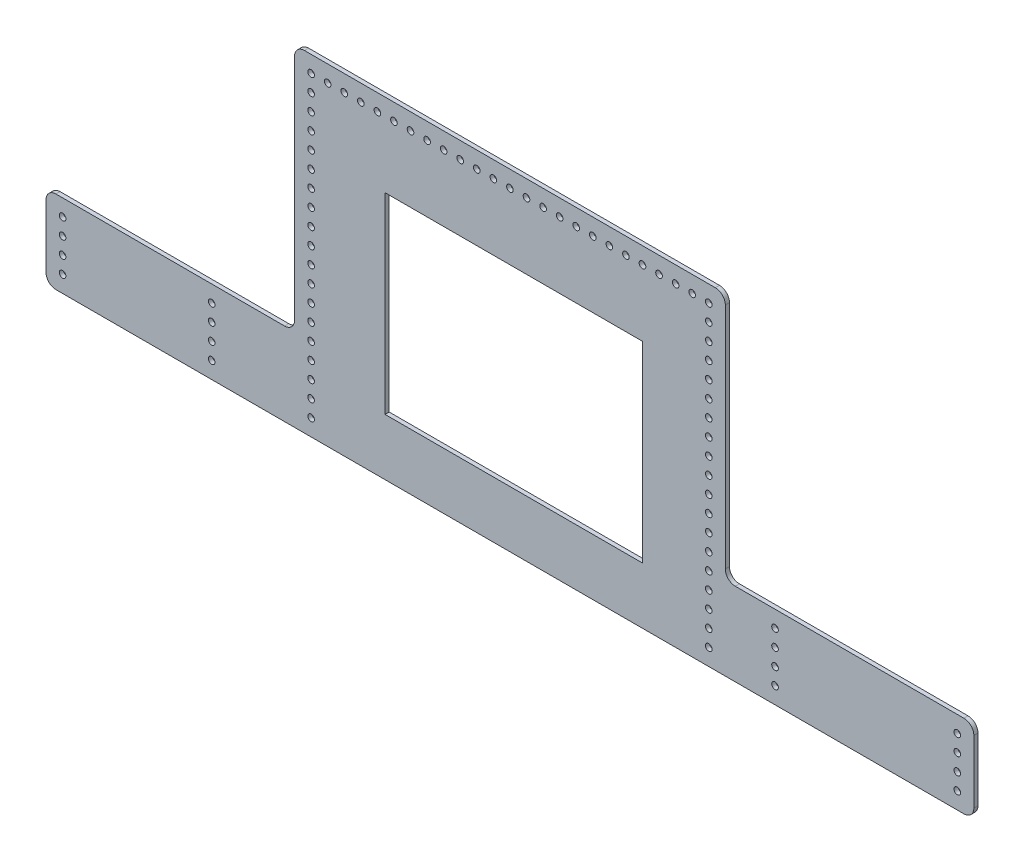
SolidWorks part; units mm, degrees
ref_plane "Front Plane" through (0, 0, 0) normal (0, 0, 1) x (1, 0, 0)
ref_plane "Top Plane" through (0, 0, 0) normal (0, 1, 0) x (1, 0, 0)
ref_plane "Right Plane" through (0, 0, 0) normal (1, 0, 0) x (0, 0, -1)
sketch "Sketch1" plane through (0, 0, 0) normal (0, 0, 1) x (1, 0, 0)
  line L1 (-309.8201, -121.697) -> (401.3799, -121.697)
  line L2 (-309.8201, -121.697) -> (-309.8201, -58.197)
  line L3 (-119.3201, 132.303) -> (210.8799, 132.303)
  line L4 (401.3799, -121.697) -> (401.3799, -58.197)
  line L11 (-309.8201, -58.197) -> (-119.3201, -58.197)
  line L12 (-119.3201, 132.303) -> (-119.3201, -58.197)
  line L15 (401.3799, -58.197) -> (210.8799, -58.197)
  line L16 (210.8799, 132.303) -> (210.8799, -58.197)
  line L17 (-49.9208, 68.803) -> (147.3799, 68.803)
  line L18 (-49.9208, 68.803) -> (-49.9208, -78.3706)
  line L19 (-49.9208, -78.3706) -> (147.3799, -78.3706)
  line L20 (147.3799, 68.803) -> (147.3799, -78.3706)
  circle A0 centre (-297.1201, -70.897) radius 2.54
  circle A1 centre (388.6799, -70.897) radius 2.54
  circle A2 centre (388.6799, -83.597) radius 2.54
  circle A3 centre (388.6799, -96.297) radius 2.54
  circle A4 centre (388.6799, -108.997) radius 2.54
  circle A6 centre (-297.1201, -83.597) radius 2.54
  circle A7 centre (-297.1201, -96.297) radius 2.54
  circle A8 centre (-297.1201, -108.997) radius 2.54
  circle A73 centre (-182.8201, -70.897) radius 2.54
  circle A74 centre (248.9799, -70.897) radius 2.54
  circle A75 centre (-297.1201, -121.697) radius 2.54 [skipped]
  circle A76 centre (388.6799, -121.697) radius 2.54 [skipped]
  circle A77 centre (248.9799, -83.597) radius 2.54
  circle A78 centre (248.9799, -96.297) radius 2.54
  circle A79 centre (248.9799, -108.997) radius 2.54
  circle A80 centre (-182.8201, -83.597) radius 2.54
  circle A86 centre (-182.8201, -96.297) radius 2.54
  circle A87 centre (-182.8201, -108.997) radius 2.54
  circle A104 centre (-106.6201, 119.603) radius 2.54
  circle A105 centre (-93.9201, 119.603) radius 2.54
  circle A106 centre (-81.2201, 119.603) radius 2.54
  circle A107 centre (-68.5201, 119.603) radius 2.54
  circle A108 centre (-55.8201, 119.603) radius 2.54
  circle A109 centre (-43.1201, 119.603) radius 2.54
  circle A110 centre (-30.4201, 119.603) radius 2.54
  circle A111 centre (-17.7201, 119.603) radius 2.54
  circle A112 centre (-5.0201, 119.603) radius 2.54
  circle A113 centre (7.6799, 119.603) radius 2.54
  circle A114 centre (20.3799, 119.603) radius 2.54
  circle A115 centre (33.0799, 119.603) radius 2.54
  circle A116 centre (45.7799, 119.603) radius 2.54
  circle A117 centre (58.4799, 119.603) radius 2.54
  circle A118 centre (71.1799, 119.603) radius 2.54
  circle A119 centre (83.8799, 119.603) radius 2.54
  circle A120 centre (96.5799, 119.603) radius 2.54
  circle A121 centre (109.2799, 119.603) radius 2.54
  circle A122 centre (121.9799, 119.603) radius 2.54
  circle A123 centre (134.6799, 119.603) radius 2.54
  circle A124 centre (147.3799, 119.603) radius 2.54
  circle A125 centre (160.0799, 119.603) radius 2.54
  circle A126 centre (172.7799, 119.603) radius 2.54
  circle A127 centre (185.4799, 119.603) radius 2.54
  circle A128 centre (198.1799, 119.603) radius 2.54
  circle A152 centre (198.1799, 106.903) radius 2.54
  circle A176 centre (198.1799, 94.203) radius 2.54
  circle A200 centre (198.1799, 81.503) radius 2.54
  circle A224 centre (198.1799, 68.803) radius 2.54
  circle A248 centre (198.1799, 56.103) radius 2.54
  circle A272 centre (198.1799, 43.403) radius 2.54
  circle A296 centre (198.1799, 30.703) radius 2.54
  circle A320 centre (198.1799, 18.003) radius 2.54
  circle A344 centre (198.1799, 5.303) radius 2.54
  circle A368 centre (198.1799, -7.397) radius 2.54
  circle A392 centre (198.1799, -20.097) radius 2.54
  circle A416 centre (198.1799, -32.797) radius 2.54
  circle A440 centre (198.1799, -45.497) radius 2.54
  circle A464 centre (198.1799, -58.197) radius 2.54
  circle A488 centre (198.1799, -70.897) radius 2.54
  circle A512 centre (198.1799, -83.597) radius 2.54
  circle A536 centre (198.1799, -96.297) radius 2.54
  circle A560 centre (198.1799, -108.997) radius 2.54
  circle A561 centre (-106.6201, 106.903) radius 2.54
  circle A562 centre (-106.6201, 94.203) radius 2.54
  circle A563 centre (-106.6201, 81.503) radius 2.54
  circle A564 centre (-106.6201, 68.803) radius 2.54
  circle A565 centre (-106.6201, 56.103) radius 2.54
  circle A566 centre (-106.6201, 43.403) radius 2.54
  circle A567 centre (-106.6201, 30.703) radius 2.54
  circle A568 centre (-106.6201, 18.003) radius 2.54
  circle A569 centre (-106.6201, 5.303) radius 2.54
  circle A570 centre (-106.6201, -7.397) radius 2.54
  circle A571 centre (-106.6201, -20.097) radius 2.54
  circle A572 centre (-106.6201, -32.797) radius 2.54
  circle A573 centre (-106.6201, -45.497) radius 2.54
  circle A574 centre (-106.6201, -58.197) radius 2.54
  circle A575 centre (-106.6201, -70.897) radius 2.54
  circle A576 centre (-106.6201, -83.597) radius 2.54
  circle A577 centre (-106.6201, -96.297) radius 2.54
  circle A578 centre (-106.6201, -108.997) radius 2.54
  circle A579 centre (-93.9201, 106.903) radius 2.54 [skipped]
  circle A580 centre (-81.2201, 106.903) radius 2.54 [skipped]
  circle A581 centre (-68.5201, 106.903) radius 2.54 [skipped]
  circle A582 centre (-55.8201, 106.903) radius 2.54 [skipped]
  circle A583 centre (-43.1201, 106.903) radius 2.54 [skipped]
  circle A584 centre (-30.4201, 106.903) radius 2.54 [skipped]
  circle A585 centre (-17.7201, 106.903) radius 2.54 [skipped]
  circle A586 centre (-5.0201, 106.903) radius 2.54 [skipped]
  circle A587 centre (7.6799, 106.903) radius 2.54 [skipped]
  circle A588 centre (20.3799, 106.903) radius 2.54 [skipped]
  circle A589 centre (33.0799, 106.903) radius 2.54 [skipped]
  circle A590 centre (45.7799, 106.903) radius 2.54 [skipped]
  circle A591 centre (58.4799, 106.903) radius 2.54 [skipped]
  circle A592 centre (71.1799, 106.903) radius 2.54 [skipped]
  circle A593 centre (83.8799, 106.903) radius 2.54 [skipped]
  circle A594 centre (96.5799, 106.903) radius 2.54 [skipped]
  circle A595 centre (109.2799, 106.903) radius 2.54 [skipped]
  circle A596 centre (121.9799, 106.903) radius 2.54 [skipped]
  circle A597 centre (134.6799, 106.903) radius 2.54 [skipped]
  circle A598 centre (147.3799, 106.903) radius 2.54 [skipped]
  circle A599 centre (160.0799, 106.903) radius 2.54 [skipped]
  circle A600 centre (172.7799, 106.903) radius 2.54 [skipped]
  circle A601 centre (185.4799, 106.903) radius 2.54 [skipped]
  circle A602 centre (-93.9201, 94.203) radius 2.54 [skipped]
  circle A603 centre (-81.2201, 94.203) radius 2.54 [skipped]
  circle A604 centre (-68.5201, 94.203) radius 2.54 [skipped]
  circle A605 centre (-55.8201, 94.203) radius 2.54 [skipped]
  circle A606 centre (-43.1201, 94.203) radius 2.54 [skipped]
  circle A607 centre (-30.4201, 94.203) radius 2.54 [skipped]
  circle A608 centre (-17.7201, 94.203) radius 2.54 [skipped]
  circle A609 centre (-5.0201, 94.203) radius 2.54 [skipped]
  circle A610 centre (7.6799, 94.203) radius 2.54 [skipped]
  circle A611 centre (20.3799, 94.203) radius 2.54 [skipped]
  circle A612 centre (33.0799, 94.203) radius 2.54 [skipped]
  circle A613 centre (45.7799, 94.203) radius 2.54 [skipped]
  circle A614 centre (58.4799, 94.203) radius 2.54 [skipped]
  circle A615 centre (71.1799, 94.203) radius 2.54 [skipped]
  circle A616 centre (83.8799, 94.203) radius 2.54 [skipped]
  circle A617 centre (96.5799, 94.203) radius 2.54 [skipped]
  circle A618 centre (109.2799, 94.203) radius 2.54 [skipped]
  circle A619 centre (121.9799, 94.203) radius 2.54 [skipped]
  circle A620 centre (134.6799, 94.203) radius 2.54 [skipped]
  circle A621 centre (147.3799, 94.203) radius 2.54 [skipped]
  circle A622 centre (160.0799, 94.203) radius 2.54 [skipped]
  circle A623 centre (172.7799, 94.203) radius 2.54 [skipped]
  circle A624 centre (185.4799, 94.203) radius 2.54 [skipped]
  circle A625 centre (-93.9201, 81.503) radius 2.54 [skipped]
  circle A626 centre (-81.2201, 81.503) radius 2.54 [skipped]
  circle A627 centre (-68.5201, 81.503) radius 2.54 [skipped]
  circle A628 centre (-55.8201, 81.503) radius 2.54 [skipped]
  circle A629 centre (-43.1201, 81.503) radius 2.54 [skipped]
  circle A630 centre (-30.4201, 81.503) radius 2.54 [skipped]
  circle A631 centre (-17.7201, 81.503) radius 2.54 [skipped]
  circle A632 centre (-5.0201, 81.503) radius 2.54 [skipped]
  circle A633 centre (7.6799, 81.503) radius 2.54 [skipped]
  circle A634 centre (20.3799, 81.503) radius 2.54 [skipped]
  circle A635 centre (33.0799, 81.503) radius 2.54 [skipped]
  circle A636 centre (45.7799, 81.503) radius 2.54 [skipped]
  circle A637 centre (58.4799, 81.503) radius 2.54 [skipped]
  circle A638 centre (71.1799, 81.503) radius 2.54 [skipped]
  circle A639 centre (83.8799, 81.503) radius 2.54 [skipped]
  circle A640 centre (96.5799, 81.503) radius 2.54 [skipped]
  circle A641 centre (109.2799, 81.503) radius 2.54 [skipped]
  circle A642 centre (121.9799, 81.503) radius 2.54 [skipped]
  circle A643 centre (134.6799, 81.503) radius 2.54 [skipped]
  circle A644 centre (147.3799, 81.503) radius 2.54 [skipped]
  circle A645 centre (160.0799, 81.503) radius 2.54 [skipped]
  circle A646 centre (172.7799, 81.503) radius 2.54 [skipped]
  circle A647 centre (185.4799, 81.503) radius 2.54 [skipped]
  circle A648 centre (-93.9201, 68.803) radius 2.54 [skipped]
  circle A649 centre (-81.2201, 68.803) radius 2.54 [skipped]
  circle A650 centre (-68.5201, 68.803) radius 2.54 [skipped]
  circle A651 centre (-55.8201, 68.803) radius 2.54 [skipped]
  circle A652 centre (-43.1201, 68.803) radius 2.54 [skipped]
  circle A653 centre (-30.4201, 68.803) radius 2.54 [skipped]
  circle A654 centre (-17.7201, 68.803) radius 2.54 [skipped]
  circle A655 centre (-5.0201, 68.803) radius 2.54 [skipped]
  circle A656 centre (7.6799, 68.803) radius 2.54 [skipped]
  circle A657 centre (20.3799, 68.803) radius 2.54 [skipped]
  circle A658 centre (33.0799, 68.803) radius 2.54 [skipped]
  circle A659 centre (45.7799, 68.803) radius 2.54 [skipped]
  circle A660 centre (58.4799, 68.803) radius 2.54 [skipped]
  circle A661 centre (71.1799, 68.803) radius 2.54 [skipped]
  circle A662 centre (83.8799, 68.803) radius 2.54 [skipped]
  circle A663 centre (96.5799, 68.803) radius 2.54 [skipped]
  circle A664 centre (109.2799, 68.803) radius 2.54 [skipped]
  circle A665 centre (121.9799, 68.803) radius 2.54 [skipped]
  circle A666 centre (134.6799, 68.803) radius 2.54 [skipped]
  circle A667 centre (147.3799, 68.803) radius 2.54 [skipped]
  circle A668 centre (160.0799, 68.803) radius 2.54 [skipped]
  circle A669 centre (172.7799, 68.803) radius 2.54 [skipped]
  circle A670 centre (185.4799, 68.803) radius 2.54 [skipped]
  circle A671 centre (-93.9201, 56.103) radius 2.54 [skipped]
  circle A672 centre (-81.2201, 56.103) radius 2.54 [skipped]
  circle A673 centre (-68.5201, 56.103) radius 2.54 [skipped]
  circle A674 centre (-55.8201, 56.103) radius 2.54 [skipped]
  circle A675 centre (-43.1201, 56.103) radius 2.54 [skipped]
  circle A676 centre (-30.4201, 56.103) radius 2.54 [skipped]
  circle A677 centre (-17.7201, 56.103) radius 2.54 [skipped]
  circle A678 centre (-5.0201, 56.103) radius 2.54 [skipped]
  circle A679 centre (7.6799, 56.103) radius 2.54 [skipped]
  circle A680 centre (20.3799, 56.103) radius 2.54 [skipped]
  circle A681 centre (33.0799, 56.103) radius 2.54 [skipped]
  circle A682 centre (45.7799, 56.103) radius 2.54 [skipped]
  circle A683 centre (58.4799, 56.103) radius 2.54 [skipped]
  circle A684 centre (71.1799, 56.103) radius 2.54 [skipped]
  circle A685 centre (83.8799, 56.103) radius 2.54 [skipped]
  circle A686 centre (96.5799, 56.103) radius 2.54 [skipped]
  circle A687 centre (109.2799, 56.103) radius 2.54 [skipped]
  circle A688 centre (121.9799, 56.103) radius 2.54 [skipped]
  circle A689 centre (134.6799, 56.103) radius 2.54 [skipped]
  circle A690 centre (147.3799, 56.103) radius 2.54 [skipped]
  circle A691 centre (160.0799, 56.103) radius 2.54 [skipped]
  circle A692 centre (172.7799, 56.103) radius 2.54 [skipped]
  circle A693 centre (185.4799, 56.103) radius 2.54 [skipped]
  circle A694 centre (-93.9201, 43.403) radius 2.54 [skipped]
  circle A695 centre (-81.2201, 43.403) radius 2.54 [skipped]
  circle A696 centre (-68.5201, 43.403) radius 2.54 [skipped]
  circle A697 centre (-55.8201, 43.403) radius 2.54 [skipped]
  circle A698 centre (-43.1201, 43.403) radius 2.54 [skipped]
  circle A699 centre (-30.4201, 43.403) radius 2.54 [skipped]
  circle A700 centre (-17.7201, 43.403) radius 2.54 [skipped]
  circle A701 centre (-5.0201, 43.403) radius 2.54 [skipped]
  circle A702 centre (7.6799, 43.403) radius 2.54 [skipped]
  circle A703 centre (20.3799, 43.403) radius 2.54 [skipped]
  circle A704 centre (33.0799, 43.403) radius 2.54 [skipped]
  circle A705 centre (45.7799, 43.403) radius 2.54 [skipped]
  circle A706 centre (58.4799, 43.403) radius 2.54 [skipped]
  circle A707 centre (71.1799, 43.403) radius 2.54 [skipped]
  circle A708 centre (83.8799, 43.403) radius 2.54 [skipped]
  circle A709 centre (96.5799, 43.403) radius 2.54 [skipped]
  circle A710 centre (109.2799, 43.403) radius 2.54 [skipped]
  circle A711 centre (121.9799, 43.403) radius 2.54 [skipped]
  circle A712 centre (134.6799, 43.403) radius 2.54 [skipped]
  circle A713 centre (147.3799, 43.403) radius 2.54 [skipped]
  circle A714 centre (160.0799, 43.403) radius 2.54 [skipped]
  circle A715 centre (172.7799, 43.403) radius 2.54 [skipped]
  circle A716 centre (185.4799, 43.403) radius 2.54 [skipped]
  circle A717 centre (-93.9201, 30.703) radius 2.54 [skipped]
  circle A718 centre (-81.2201, 30.703) radius 2.54 [skipped]
  circle A719 centre (-68.5201, 30.703) radius 2.54 [skipped]
  circle A720 centre (-55.8201, 30.703) radius 2.54 [skipped]
  circle A721 centre (-43.1201, 30.703) radius 2.54 [skipped]
  circle A722 centre (-30.4201, 30.703) radius 2.54 [skipped]
  circle A723 centre (-17.7201, 30.703) radius 2.54 [skipped]
  circle A724 centre (-5.0201, 30.703) radius 2.54 [skipped]
  circle A725 centre (7.6799, 30.703) radius 2.54 [skipped]
  circle A726 centre (20.3799, 30.703) radius 2.54 [skipped]
  circle A727 centre (33.0799, 30.703) radius 2.54 [skipped]
  circle A728 centre (45.7799, 30.703) radius 2.54 [skipped]
  circle A729 centre (58.4799, 30.703) radius 2.54 [skipped]
  circle A730 centre (71.1799, 30.703) radius 2.54 [skipped]
  circle A731 centre (83.8799, 30.703) radius 2.54 [skipped]
  circle A732 centre (96.5799, 30.703) radius 2.54 [skipped]
  circle A733 centre (109.2799, 30.703) radius 2.54 [skipped]
  circle A734 centre (121.9799, 30.703) radius 2.54 [skipped]
  circle A735 centre (134.6799, 30.703) radius 2.54 [skipped]
  circle A736 centre (147.3799, 30.703) radius 2.54 [skipped]
  circle A737 centre (160.0799, 30.703) radius 2.54 [skipped]
  circle A738 centre (172.7799, 30.703) radius 2.54 [skipped]
  circle A739 centre (-93.9201, 18.003) radius 2.54 [skipped]
  circle A740 centre (-81.2201, 18.003) radius 2.54 [skipped]
  circle A741 centre (-68.5201, 18.003) radius 2.54 [skipped]
  circle A742 centre (-55.8201, 18.003) radius 2.54 [skipped]
  circle A743 centre (-43.1201, 18.003) radius 2.54 [skipped]
  circle A744 centre (-30.4201, 18.003) radius 2.54 [skipped]
  circle A745 centre (-17.7201, 18.003) radius 2.54 [skipped]
  circle A746 centre (-5.0201, 18.003) radius 2.54 [skipped]
  circle A747 centre (7.6799, 18.003) radius 2.54 [skipped]
  circle A748 centre (20.3799, 18.003) radius 2.54 [skipped]
  circle A749 centre (33.0799, 18.003) radius 2.54 [skipped]
  circle A750 centre (45.7799, 18.003) radius 2.54 [skipped]
  circle A751 centre (58.4799, 18.003) radius 2.54 [skipped]
  circle A752 centre (71.1799, 18.003) radius 2.54 [skipped]
  circle A753 centre (83.8799, 18.003) radius 2.54 [skipped]
  circle A754 centre (96.5799, 18.003) radius 2.54 [skipped]
  circle A755 centre (109.2799, 18.003) radius 2.54 [skipped]
  circle A756 centre (121.9799, 18.003) radius 2.54 [skipped]
  circle A757 centre (134.6799, 18.003) radius 2.54 [skipped]
  circle A758 centre (147.3799, 18.003) radius 2.54 [skipped]
  circle A759 centre (160.0799, 18.003) radius 2.54 [skipped]
  circle A760 centre (172.7799, 18.003) radius 2.54 [skipped]
  circle A761 centre (185.4799, 18.003) radius 2.54 [skipped]
  circle A762 centre (-93.9201, 5.303) radius 2.54 [skipped]
  circle A763 centre (-81.2201, 5.303) radius 2.54 [skipped]
  circle A764 centre (-68.5201, 5.303) radius 2.54 [skipped]
  circle A765 centre (-55.8201, 5.303) radius 2.54 [skipped]
  circle A766 centre (-43.1201, 5.303) radius 2.54 [skipped]
  circle A767 centre (-30.4201, 5.303) radius 2.54 [skipped]
  circle A768 centre (-17.7201, 5.303) radius 2.54 [skipped]
  circle A769 centre (-5.0201, 5.303) radius 2.54 [skipped]
  circle A770 centre (7.6799, 5.303) radius 2.54 [skipped]
  circle A771 centre (20.3799, 5.303) radius 2.54 [skipped]
  circle A772 centre (33.0799, 5.303) radius 2.54 [skipped]
  circle A773 centre (45.7799, 5.303) radius 2.54 [skipped]
  circle A774 centre (58.4799, 5.303) radius 2.54 [skipped]
  circle A775 centre (71.1799, 5.303) radius 2.54 [skipped]
  circle A776 centre (83.8799, 5.303) radius 2.54 [skipped]
  circle A777 centre (96.5799, 5.303) radius 2.54 [skipped]
  circle A778 centre (109.2799, 5.303) radius 2.54 [skipped]
  circle A779 centre (121.9799, 5.303) radius 2.54 [skipped]
  circle A780 centre (134.6799, 5.303) radius 2.54 [skipped]
  circle A781 centre (147.3799, 5.303) radius 2.54 [skipped]
  circle A782 centre (160.0799, 5.303) radius 2.54 [skipped]
  circle A783 centre (172.7799, 5.303) radius 2.54 [skipped]
  circle A784 centre (185.4799, 5.303) radius 2.54 [skipped]
  circle A785 centre (-93.9201, -7.397) radius 2.54 [skipped]
  circle A786 centre (-81.2201, -7.397) radius 2.54 [skipped]
  circle A787 centre (-68.5201, -7.397) radius 2.54 [skipped]
  circle A788 centre (-55.8201, -7.397) radius 2.54 [skipped]
  circle A789 centre (-43.1201, -7.397) radius 2.54 [skipped]
  circle A790 centre (-30.4201, -7.397) radius 2.54 [skipped]
  circle A791 centre (-17.7201, -7.397) radius 2.54 [skipped]
  circle A792 centre (-5.0201, -7.397) radius 2.54 [skipped]
  circle A793 centre (7.6799, -7.397) radius 2.54 [skipped]
  circle A794 centre (20.3799, -7.397) radius 2.54 [skipped]
  circle A795 centre (33.0799, -7.397) radius 2.54 [skipped]
  circle A796 centre (45.7799, -7.397) radius 2.54 [skipped]
  circle A797 centre (58.4799, -7.397) radius 2.54 [skipped]
  circle A798 centre (71.1799, -7.397) radius 2.54 [skipped]
  circle A799 centre (83.8799, -7.397) radius 2.54 [skipped]
  circle A800 centre (96.5799, -7.397) radius 2.54 [skipped]
  circle A801 centre (109.2799, -7.397) radius 2.54 [skipped]
  circle A802 centre (121.9799, -7.397) radius 2.54 [skipped]
  circle A803 centre (134.6799, -7.397) radius 2.54 [skipped]
  circle A804 centre (147.3799, -7.397) radius 2.54 [skipped]
  circle A805 centre (160.0799, -7.397) radius 2.54 [skipped]
  circle A806 centre (172.7799, -7.397) radius 2.54 [skipped]
  circle A807 centre (185.4799, -7.397) radius 2.54 [skipped]
  circle A808 centre (-93.9201, -20.097) radius 2.54 [skipped]
  circle A809 centre (-81.2201, -20.097) radius 2.54 [skipped]
  circle A810 centre (-68.5201, -20.097) radius 2.54 [skipped]
  circle A811 centre (-55.8201, -20.097) radius 2.54 [skipped]
  circle A812 centre (-43.1201, -20.097) radius 2.54 [skipped]
  circle A813 centre (-30.4201, -20.097) radius 2.54 [skipped]
  circle A814 centre (-17.7201, -20.097) radius 2.54 [skipped]
  circle A815 centre (-5.0201, -20.097) radius 2.54 [skipped]
  circle A816 centre (7.6799, -20.097) radius 2.54 [skipped]
  circle A817 centre (20.3799, -20.097) radius 2.54 [skipped]
  circle A818 centre (33.0799, -20.097) radius 2.54 [skipped]
  circle A819 centre (45.7799, -20.097) radius 2.54 [skipped]
  circle A820 centre (58.4799, -20.097) radius 2.54 [skipped]
  circle A821 centre (71.1799, -20.097) radius 2.54 [skipped]
  circle A822 centre (83.8799, -20.097) radius 2.54 [skipped]
  circle A823 centre (96.5799, -20.097) radius 2.54 [skipped]
  circle A824 centre (109.2799, -20.097) radius 2.54 [skipped]
  circle A825 centre (121.9799, -20.097) radius 2.54 [skipped]
  circle A826 centre (134.6799, -20.097) radius 2.54 [skipped]
  circle A827 centre (147.3799, -20.097) radius 2.54 [skipped]
  circle A828 centre (160.0799, -20.097) radius 2.54 [skipped]
  circle A829 centre (172.7799, -20.097) radius 2.54 [skipped]
  circle A830 centre (185.4799, -20.097) radius 2.54 [skipped]
  circle A831 centre (-93.9201, -32.797) radius 2.54 [skipped]
  circle A832 centre (-81.2201, -32.797) radius 2.54 [skipped]
  circle A833 centre (-68.5201, -32.797) radius 2.54 [skipped]
  circle A834 centre (-55.8201, -32.797) radius 2.54 [skipped]
  circle A835 centre (-43.1201, -32.797) radius 2.54 [skipped]
  circle A836 centre (-30.4201, -32.797) radius 2.54 [skipped]
  circle A837 centre (-17.7201, -32.797) radius 2.54 [skipped]
  circle A838 centre (-5.0201, -32.797) radius 2.54 [skipped]
  circle A839 centre (7.6799, -32.797) radius 2.54 [skipped]
  circle A840 centre (20.3799, -32.797) radius 2.54 [skipped]
  circle A841 centre (33.0799, -32.797) radius 2.54 [skipped]
  circle A842 centre (45.7799, -32.797) radius 2.54 [skipped]
  circle A843 centre (58.4799, -32.797) radius 2.54 [skipped]
  circle A844 centre (71.1799, -32.797) radius 2.54 [skipped]
  circle A845 centre (83.8799, -32.797) radius 2.54 [skipped]
  circle A846 centre (96.5799, -32.797) radius 2.54 [skipped]
  circle A847 centre (109.2799, -32.797) radius 2.54 [skipped]
  circle A848 centre (121.9799, -32.797) radius 2.54 [skipped]
  circle A849 centre (134.6799, -32.797) radius 2.54 [skipped]
  circle A850 centre (147.3799, -32.797) radius 2.54 [skipped]
  circle A851 centre (160.0799, -32.797) radius 2.54 [skipped]
  circle A852 centre (172.7799, -32.797) radius 2.54 [skipped]
  circle A853 centre (185.4799, -32.797) radius 2.54 [skipped]
  circle A854 centre (-93.9201, -45.497) radius 2.54 [skipped]
  circle A855 centre (-81.2201, -45.497) radius 2.54 [skipped]
  circle A856 centre (-68.5201, -45.497) radius 2.54 [skipped]
  circle A857 centre (-55.8201, -45.497) radius 2.54 [skipped]
  circle A858 centre (-43.1201, -45.497) radius 2.54 [skipped]
  circle A859 centre (-30.4201, -45.497) radius 2.54 [skipped]
  circle A860 centre (-17.7201, -45.497) radius 2.54 [skipped]
  circle A861 centre (-5.0201, -45.497) radius 2.54 [skipped]
  circle A862 centre (7.6799, -45.497) radius 2.54 [skipped]
  circle A863 centre (20.3799, -45.497) radius 2.54 [skipped]
  circle A864 centre (33.0799, -45.497) radius 2.54 [skipped]
  circle A865 centre (45.7799, -45.497) radius 2.54 [skipped]
  circle A866 centre (58.4799, -45.497) radius 2.54 [skipped]
  circle A867 centre (71.1799, -45.497) radius 2.54 [skipped]
  circle A868 centre (83.8799, -45.497) radius 2.54 [skipped]
  circle A869 centre (96.5799, -45.497) radius 2.54 [skipped]
  circle A870 centre (109.2799, -45.497) radius 2.54 [skipped]
  circle A871 centre (121.9799, -45.497) radius 2.54 [skipped]
  circle A872 centre (134.6799, -45.497) radius 2.54 [skipped]
  circle A873 centre (147.3799, -45.497) radius 2.54 [skipped]
  circle A874 centre (160.0799, -45.497) radius 2.54 [skipped]
  circle A875 centre (172.7799, -45.497) radius 2.54 [skipped]
  circle A876 centre (185.4799, -45.497) radius 2.54 [skipped]
  circle A877 centre (-93.9201, -58.197) radius 2.54 [skipped]
  circle A878 centre (-81.2201, -58.197) radius 2.54 [skipped]
  circle A879 centre (-68.5201, -58.197) radius 2.54 [skipped]
  circle A880 centre (-55.8201, -58.197) radius 2.54 [skipped]
  circle A881 centre (-43.1201, -58.197) radius 2.54 [skipped]
  circle A882 centre (-30.4201, -58.197) radius 2.54 [skipped]
  circle A883 centre (-17.7201, -58.197) radius 2.54 [skipped]
  circle A884 centre (-5.0201, -58.197) radius 2.54 [skipped]
  circle A885 centre (7.6799, -58.197) radius 2.54 [skipped]
  circle A886 centre (20.3799, -58.197) radius 2.54 [skipped]
  circle A887 centre (33.0799, -58.197) radius 2.54 [skipped]
  circle A888 centre (45.7799, -58.197) radius 2.54 [skipped]
  circle A889 centre (58.4799, -58.197) radius 2.54 [skipped]
  circle A890 centre (71.1799, -58.197) radius 2.54 [skipped]
  circle A891 centre (83.8799, -58.197) radius 2.54 [skipped]
  circle A892 centre (96.5799, -58.197) radius 2.54 [skipped]
  circle A893 centre (109.2799, -58.197) radius 2.54 [skipped]
  circle A894 centre (121.9799, -58.197) radius 2.54 [skipped]
  circle A895 centre (134.6799, -58.197) radius 2.54 [skipped]
  circle A896 centre (147.3799, -58.197) radius 2.54 [skipped]
  circle A897 centre (160.0799, -58.197) radius 2.54 [skipped]
  circle A898 centre (172.7799, -58.197) radius 2.54 [skipped]
  circle A899 centre (185.4799, -58.197) radius 2.54 [skipped]
  circle A900 centre (-93.9201, -70.897) radius 2.54 [skipped]
  circle A901 centre (-81.2201, -70.897) radius 2.54 [skipped]
  circle A902 centre (-68.5201, -70.897) radius 2.54 [skipped]
  circle A903 centre (-55.8201, -70.897) radius 2.54 [skipped]
  circle A904 centre (-43.1201, -70.897) radius 2.54 [skipped]
  circle A905 centre (-30.4201, -70.897) radius 2.54 [skipped]
  circle A906 centre (-17.7201, -70.897) radius 2.54 [skipped]
  circle A907 centre (-5.0201, -70.897) radius 2.54 [skipped]
  circle A908 centre (7.6799, -70.897) radius 2.54 [skipped]
  circle A909 centre (20.3799, -70.897) radius 2.54 [skipped]
  circle A910 centre (33.0799, -70.897) radius 2.54 [skipped]
  circle A911 centre (45.7799, -70.897) radius 2.54 [skipped]
  circle A912 centre (58.4799, -70.897) radius 2.54 [skipped]
  circle A913 centre (71.1799, -70.897) radius 2.54 [skipped]
  circle A914 centre (83.8799, -70.897) radius 2.54 [skipped]
  circle A915 centre (96.5799, -70.897) radius 2.54 [skipped]
  circle A916 centre (109.2799, -70.897) radius 2.54 [skipped]
  circle A917 centre (121.9799, -70.897) radius 2.54 [skipped]
  circle A918 centre (134.6799, -70.897) radius 2.54 [skipped]
  circle A919 centre (147.3799, -70.897) radius 2.54 [skipped]
  circle A920 centre (160.0799, -70.897) radius 2.54 [skipped]
  circle A921 centre (172.7799, -70.897) radius 2.54 [skipped]
  circle A922 centre (185.4799, -70.897) radius 2.54 [skipped]
  circle A923 centre (-93.9201, -83.597) radius 2.54 [skipped]
  circle A924 centre (-81.2201, -83.597) radius 2.54 [skipped]
  circle A925 centre (-68.5201, -83.597) radius 2.54 [skipped]
  circle A926 centre (-55.8201, -83.597) radius 2.54 [skipped]
  circle A927 centre (-43.1201, -83.597) radius 2.54 [skipped]
  circle A928 centre (-30.4201, -83.597) radius 2.54 [skipped]
  circle A929 centre (-17.7201, -83.597) radius 2.54 [skipped]
  circle A930 centre (-5.0201, -83.597) radius 2.54 [skipped]
  circle A931 centre (7.6799, -83.597) radius 2.54 [skipped]
  circle A932 centre (20.3799, -83.597) radius 2.54 [skipped]
  circle A933 centre (33.0799, -83.597) radius 2.54 [skipped]
  circle A934 centre (45.7799, -83.597) radius 2.54 [skipped]
  circle A935 centre (58.4799, -83.597) radius 2.54 [skipped]
  circle A936 centre (71.1799, -83.597) radius 2.54 [skipped]
  circle A937 centre (83.8799, -83.597) radius 2.54 [skipped]
  circle A938 centre (96.5799, -83.597) radius 2.54 [skipped]
  circle A939 centre (109.2799, -83.597) radius 2.54 [skipped]
  circle A940 centre (121.9799, -83.597) radius 2.54 [skipped]
  circle A941 centre (134.6799, -83.597) radius 2.54 [skipped]
  circle A942 centre (147.3799, -83.597) radius 2.54 [skipped]
  circle A943 centre (160.0799, -83.597) radius 2.54 [skipped]
  circle A944 centre (172.7799, -83.597) radius 2.54 [skipped]
  circle A945 centre (185.4799, -83.597) radius 2.54 [skipped]
  circle A946 centre (-93.9201, -96.297) radius 2.54 [skipped]
  circle A947 centre (-81.2201, -96.297) radius 2.54 [skipped]
  circle A948 centre (-68.5201, -96.297) radius 2.54 [skipped]
  circle A949 centre (-55.8201, -96.297) radius 2.54 [skipped]
  circle A950 centre (-43.1201, -96.297) radius 2.54 [skipped]
  circle A951 centre (-30.4201, -96.297) radius 2.54 [skipped]
  circle A952 centre (-17.7201, -96.297) radius 2.54 [skipped]
  circle A953 centre (-5.0201, -96.297) radius 2.54 [skipped]
  circle A954 centre (7.6799, -96.297) radius 2.54 [skipped]
  circle A955 centre (20.3799, -96.297) radius 2.54 [skipped]
  circle A956 centre (33.0799, -96.297) radius 2.54 [skipped]
  circle A957 centre (45.7799, -96.297) radius 2.54 [skipped]
  circle A958 centre (58.4799, -96.297) radius 2.54 [skipped]
  circle A959 centre (71.1799, -96.297) radius 2.54 [skipped]
  circle A960 centre (83.8799, -96.297) radius 2.54 [skipped]
  circle A961 centre (96.5799, -96.297) radius 2.54 [skipped]
  circle A962 centre (109.2799, -96.297) radius 2.54 [skipped]
  circle A963 centre (121.9799, -96.297) radius 2.54 [skipped]
  circle A964 centre (134.6799, -96.297) radius 2.54 [skipped]
  circle A965 centre (147.3799, -96.297) radius 2.54 [skipped]
  circle A966 centre (160.0799, -96.297) radius 2.54 [skipped]
  circle A967 centre (172.7799, -96.297) radius 2.54 [skipped]
  circle A968 centre (185.4799, -96.297) radius 2.54 [skipped]
  circle A969 centre (-93.9201, -108.997) radius 2.54 [skipped]
  circle A970 centre (-81.2201, -108.997) radius 2.54 [skipped]
  circle A971 centre (-68.5201, -108.997) radius 2.54 [skipped]
  circle A972 centre (-55.8201, -108.997) radius 2.54 [skipped]
  circle A973 centre (-43.1201, -108.997) radius 2.54 [skipped]
  circle A974 centre (-30.4201, -108.997) radius 2.54 [skipped]
  circle A975 centre (-17.7201, -108.997) radius 2.54 [skipped]
  circle A976 centre (-5.0201, -108.997) radius 2.54 [skipped]
  circle A977 centre (7.6799, -108.997) radius 2.54 [skipped]
  circle A978 centre (20.3799, -108.997) radius 2.54 [skipped]
  circle A979 centre (33.0799, -108.997) radius 2.54 [skipped]
  circle A980 centre (45.7799, -108.997) radius 2.54 [skipped]
  circle A981 centre (58.4799, -108.997) radius 2.54 [skipped]
  circle A982 centre (71.1799, -108.997) radius 2.54 [skipped]
  circle A983 centre (83.8799, -108.997) radius 2.54 [skipped]
  circle A984 centre (96.5799, -108.997) radius 2.54 [skipped]
  circle A985 centre (109.2799, -108.997) radius 2.54 [skipped]
  circle A986 centre (121.9799, -108.997) radius 2.54 [skipped]
  circle A987 centre (134.6799, -108.997) radius 2.54 [skipped]
  circle A988 centre (147.3799, -108.997) radius 2.54 [skipped]
  circle A989 centre (160.0799, -108.997) radius 2.54 [skipped]
  circle A990 centre (172.7799, -108.997) radius 2.54 [skipped]
  circle A991 centre (185.4799, -108.997) radius 2.54 [skipped]
  circle A992 centre (185.4799, 30.703) radius 2.54 [skipped]
  dimension "D7" = 12.7
  dimension "D11" = 12.7
  dimension "D17" = 2
  dimension "D18" = 4
  dimension "D13" = 19
  dimension "D15" = 127
  dimension "D1" = 711.2
  dimension "D2" = 254
  dimension "D3" = 190.5
  dimension "D4" = 190.5
  dimension "D5" = 190.5
  dimension "D6" = 190.5
  dimension "D8" = 12.7
  dimension "D12" = 12.7
  dimension "D16" = 12.7
  dimension "D9" = 2
  dimension "D10" = 5
  dimension "D14" = 25
extrude "Boss-Extrude1" add sketch "Sketch1" along normal blind 3.175
fillet "Fillet1" radius 7.62 1 edges at (210.8799, -58.197, 1.5875)
fillet "Fillet2" radius 7.62 5 edges at (210.8799, 132.303, 1.5875) (401.3799, -58.197, 1.5875) (401.3799, -121.697, 1.5875) (-309.8201, -121.697, 1.5875) (-309.8201, -58.197, 1.5875)
fillet "Fillet3" radius 7.62 2 edges at (-119.3201, -58.197, 1.5875) (-119.3201, 132.303, 1.5875)
